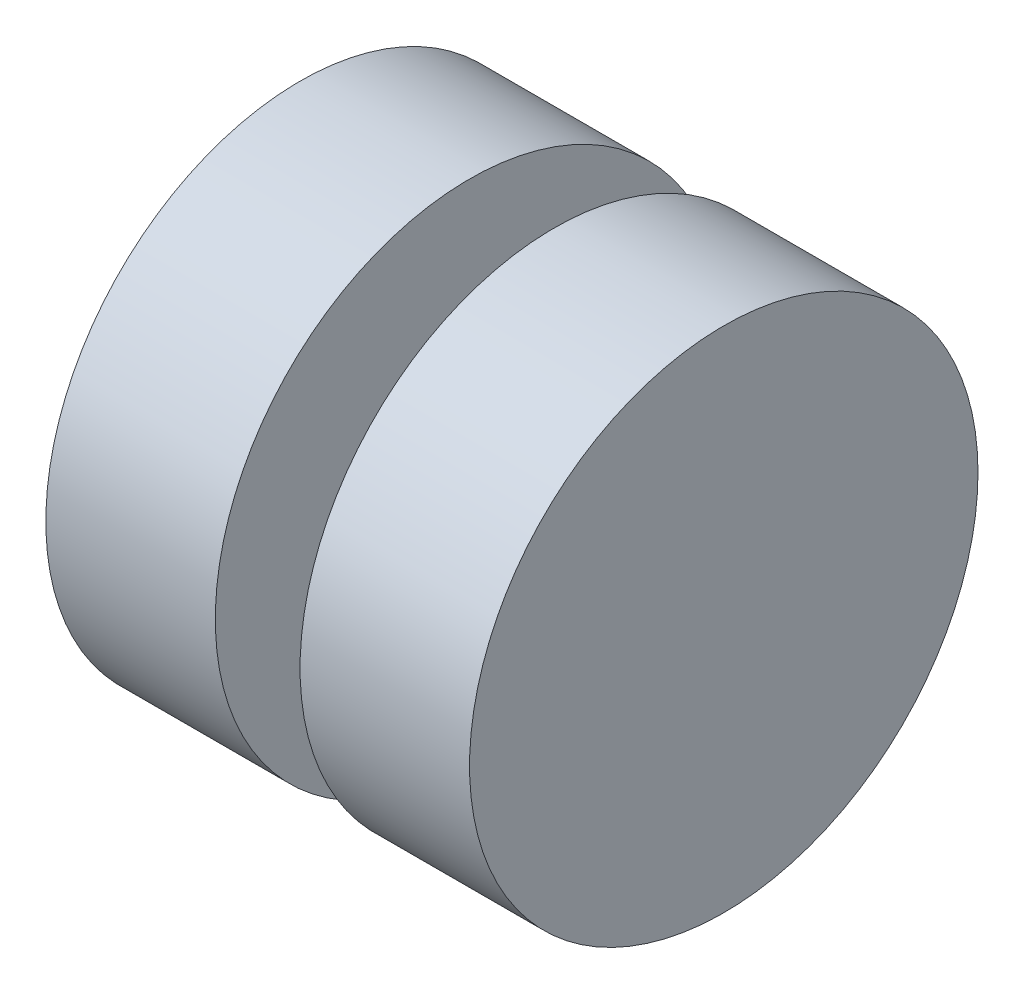
SolidWorks part; units mm, degrees
material "Aleación 1060"
ref_plane "Alzado" through (0, 0, 0) normal (0, 0, 1) x (1, 0, 0)
ref_plane "Planta" through (0, 0, 0) normal (0, 1, 0) x (1, 0, 0)
ref_plane "Vista lateral" through (0, 0, 0) normal (1, 0, 0) x (0, 0, -1)
sketch "Croquis1" plane through (0, 0, 0) normal (1, 0, 0) x (0, 0, -1)
  circle A0 centre (0, 0) radius 15
  dimension "D1" = 30
extrude "Saliente-Extruir1" add sketch "Croquis1" along normal blind 10 contours A0
sketch "Croquis2" plane through (10, 0, 0) normal (1, 0, 0) x (0, 0, -1)
  circle A0 centre (0, 0) radius 5
  dimension "D1" = 10
extrude "Saliente-Extruir2" add sketch "Croquis2" along normal blind 5
sketch "Croquis3" plane through (15, 0, 0) normal (1, 0, 0) x (0, 0, -1)
  line L0 (-5, 0) -> (-12, 0) construction
  circle A0 centre (0, 0) radius 15
  circle A1 centre (0, 0) radius 5 construction
  circle A2 centre (0, 0) radius 5 construction
  dimension "D1" = 7
extrude "Saliente-Extruir3" add sketch "Croquis3" along normal blind 10
